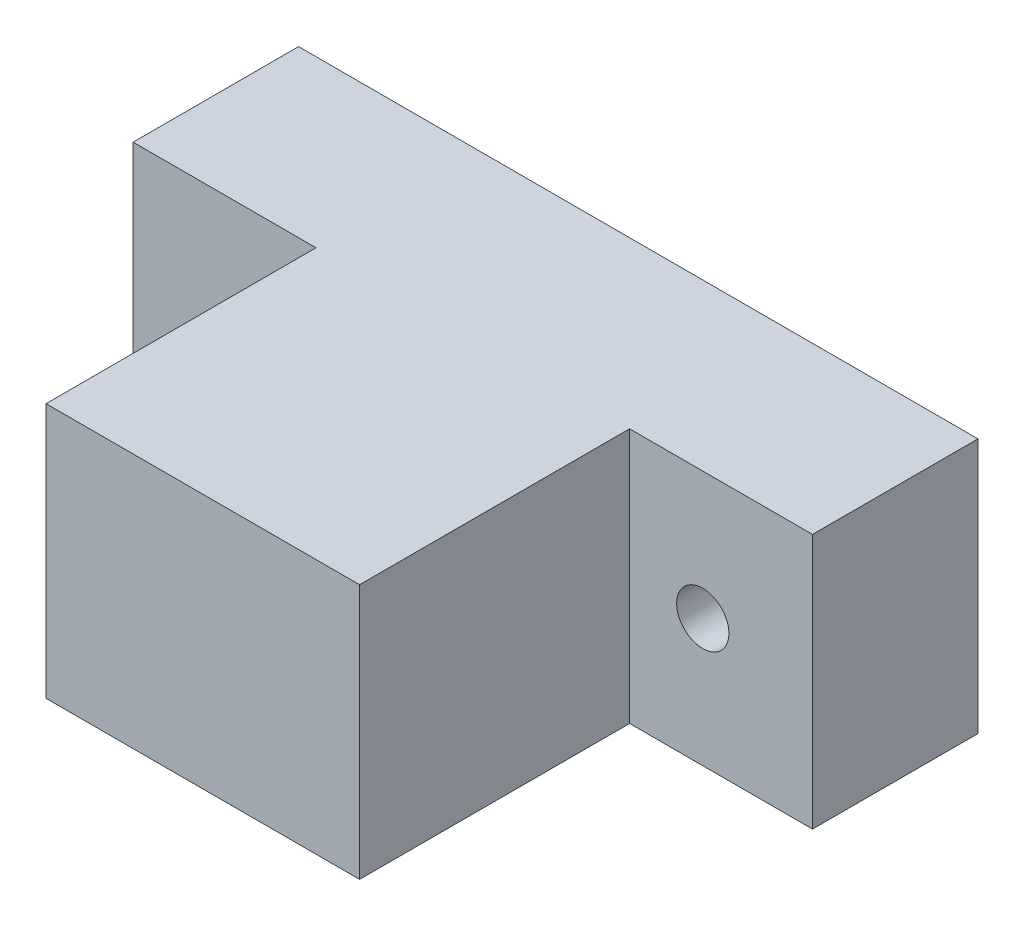
SolidWorks part; units mm, degrees
ref_plane "Front Plane" through (0, 0, 0) normal (0, 0, 1) x (1, 0, 0)
ref_plane "Top Plane" through (0, 0, 0) normal (0, 1, 0) x (1, 0, 0)
ref_plane "Right Plane" through (0, 0, 0) normal (1, 0, 0) x (0, 0, -1)
sketch "Sketch1" plane through (0, 0, 0) normal (0, 0, 1) x (1, 0, 0)
  line L1 (0, 0) -> (39, 0)
  line L2 (0, 0) -> (0, 14.65)
  line L3 (0, 14.65) -> (39, 14.65)
  line L4 (39, 0) -> (39, 14.65)
  dimension "D1" = 14.65
  dimension "D2" = 39
extrude "Boss-Extrude1" add sketch "Sketch1" along normal blind 9.5
sketch "Sketch2" plane through (0, 0, 9.5) normal (0, 0, 1) x (1, 0, 0)
  line L0 (39, 14.65) -> (0, 14.65) construction
  line L1 (10.5, 14.65) -> (28.5, 14.65)
  line L2 (10.5, 14.65) -> (10.5, 0)
  line L3 (10.5, 0) -> (28.5, 0)
  line L4 (28.5, 14.65) -> (28.5, 0)
  line L5 (0, 0) -> (39, 0) construction
  line L6 (0, 14.65) -> (0, 0) construction
  line L7 (39, 0) -> (39, 14.65) construction
  dimension "D1" = 10.5
  dimension "D2" = 10.5
extrude "Boss-Extrude2" add sketch "Sketch2" along normal blind 15.5
sketch "Sketch3" plane through (0, 0, 0) normal (0, 0, -1) x (-1, 0, 0)
  line L0 (-19.5, 14.65) -> (-19.5, 22.2713) construction
  line L1 (-39, 14.65) -> (0, 14.65) construction
  line L2 (-39, 7.325) -> (-11.5339, 7.325) construction
  line L3 (-39, 0) -> (-39, 14.65) construction
  circle A0 centre (-32.7, 7.325) radius 1.5
  circle A1 centre (-6.3, 7.325) radius 1.5
  dimension "D1" = 3
  dimension "D2" = 6.3
extrude "Cut-Extrude1" cut sketch "Sketch3" against normal blind 15.5
